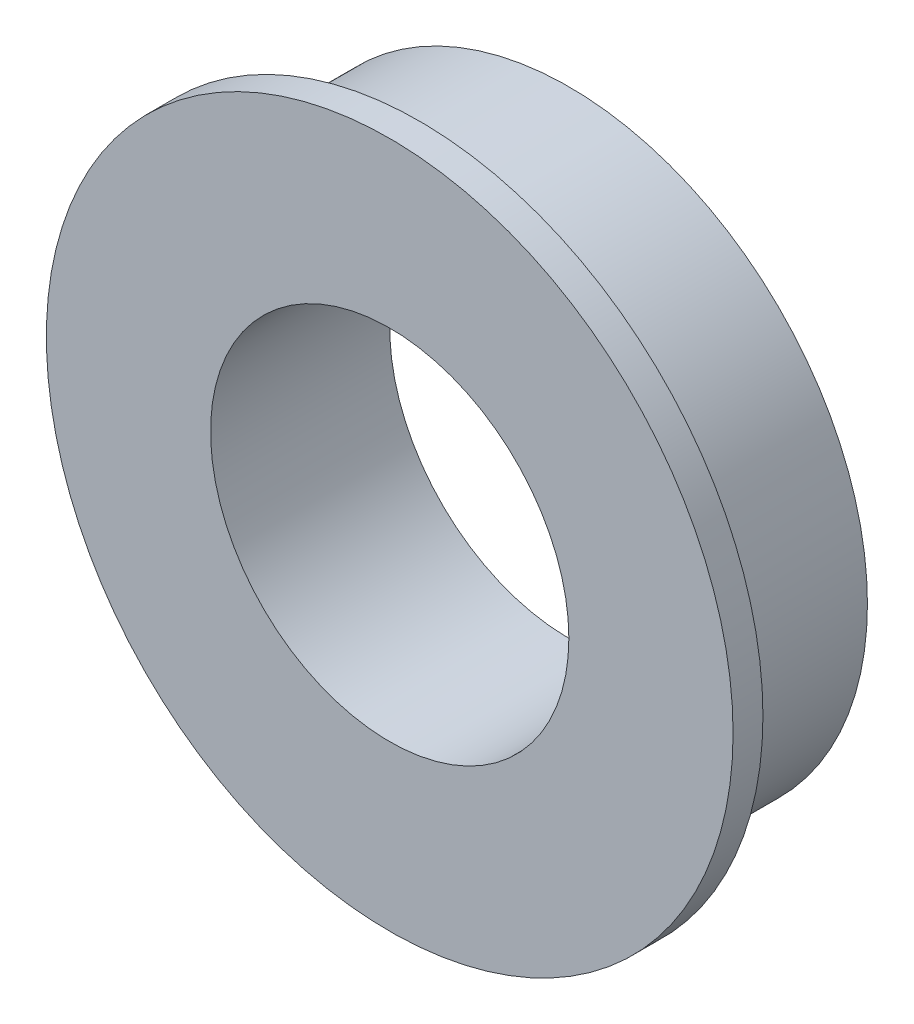
SolidWorks part; units mm, degrees
material "ｽﾃﾝﾚｽ鋼(ｸﾛﾑ)"
ref_plane "正面" through (0, 0, 0) normal (0, 0, 1) x (1, 0, 0)
ref_plane "平面" through (0, 0, 0) normal (0, 1, 0) x (1, 0, 0)
ref_plane "右側面" through (0, 0, 0) normal (1, 0, 0) x (0, 0, -1)
sketch "ｽｹｯﾁ1" plane through (0, 0, 0) normal (1, 0, 0) x (0, 0, -1)
  line L0 (0, 0) -> (50000, 0) construction
  line L1 (0, 0) -> (0, 50000) construction
  line L2 (-0.5, 5.75) -> (-0.5, 3)
  line L3 (-0.5, 3) -> (2.5, 3)
  line L4 (2.5, 3) -> (2.5, 5)
  line L5 (2.5, 5) -> (0, 5)
  line L6 (0, 5) -> (0, 5.75)
  line L7 (0, 5.75) -> (-0.5, 5.75)
  dimension "D1" = 6
  dimension "D2" = 10
  dimension "D3" = 0.5
  dimension "D4" = 3
  dimension "D5" = 11.5
revolve "回転1" add sketch "ｽｹｯﾁ1" angle 360 about L0
